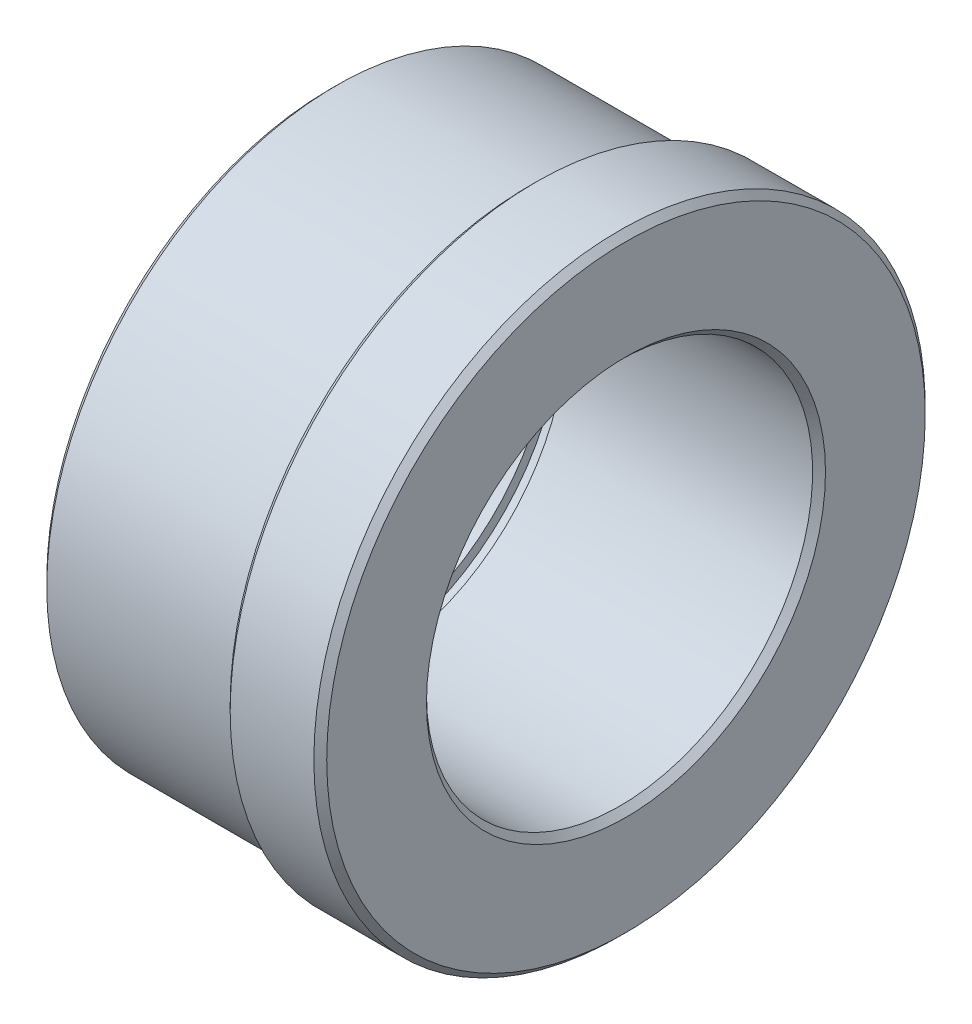
SolidWorks part; units mm, degrees
material "20"
ref_plane "前视基准面" through (0, 0, 0) normal (0, 0, 1) x (1, 0, 0)
ref_plane "上视基准面" through (0, 0, 0) normal (0, 1, 0) x (1, 0, 0)
ref_plane "右视基准面" through (0, 0, 0) normal (1, 0, 0) x (0, 0, -1)
sketch "草图1" plane through (0, 0, 0) normal (0, 0, 1) x (1, 0, 0)
  line L0 (0, 30) -> (0, 45)
  line L2 (46, 47.5) -> (46, 30)
  line L3 (0, 30) -> (4.5, 30)
  line L4 (4.5, 30) -> (4.5, 31.5)
  line L5 (4.5, 31.5) -> (6.7, 31.5)
  line L6 (6.7, 31.5) -> (6.7, 30)
  line L7 (6.7, 30) -> (46, 30)
  line L8 (0, 0) -> (46, 0) construction
  line L9 (0, 45) -> (31, 45)
  line L10 (31, 47.5) -> (31, 45)
  line L11 (31, 47.5) -> (46, 47.5)
  dimension "D1" = 45
  dimension "D2" = 30
  dimension "D3" = 46
  dimension "D4" = 15
  dimension "D5" = 47.5
  dimension "D6" = 4.5
  dimension "D7" = 1.5
  dimension "D8" = 2.2
revolve "旋转1" add sketch "草图1" angle 360 about L8
chamfer "倒角1" distance 1 angle 45 5 edges at (46, 0, 30) (31, 0, 47.5) (46, 0, 47.5) (0, 0, 30) (0, 0, 45)
